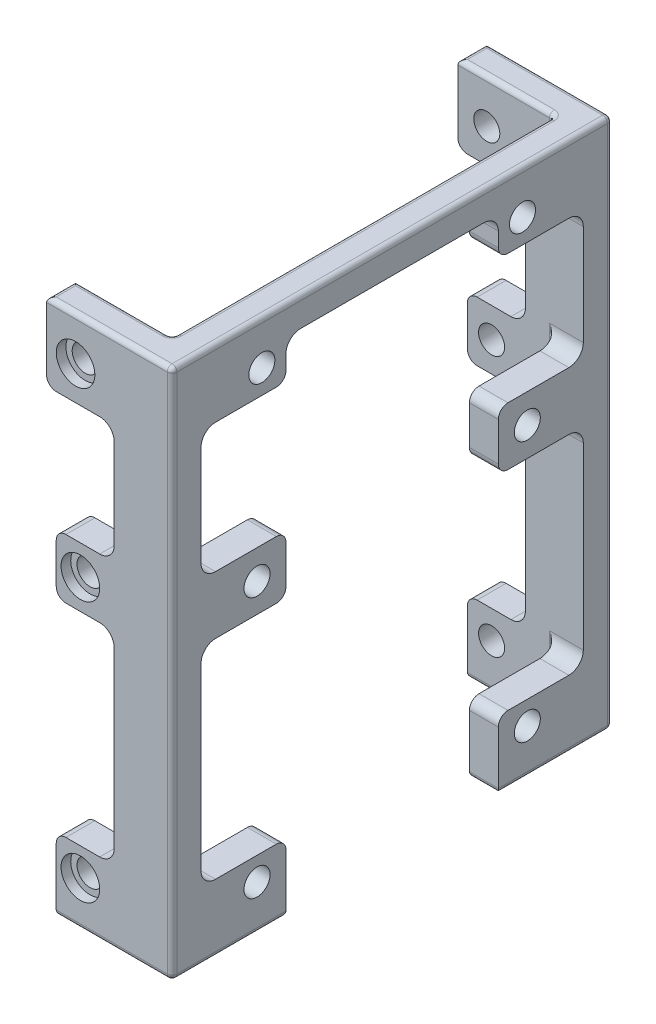
SolidWorks part; units mm, degrees
material "Esun Hard Tough Resin"
ref_plane "Front Plane" through (0, 0, 0) normal (0, 0, 1) x (1, 0, 0)
ref_plane "Top Plane" through (0, 0, 0) normal (0, 1, 0) x (1, 0, 0)
ref_plane "Right Plane" through (0, 0, 0) normal (1, 0, 0) x (0, 0, -1)
sketch "Sketch2" plane through (0, 0, 0) normal (0, 0, 1) x (1, 0, 0)
  line L0 (-6, -15.9661) -> (-6, 28)
  line L1 (6, -28) -> (-6, -28)
  line L2 (6, -28) -> (6, 28)
  line L3 (6, 28) -> (-6, 28)
  line L4 (-6, -28) -> (-6, -15.9661)
  line L5 (6, -28) -> (-6, 28) construction
  line L6 (6, 28) -> (-6, -28) construction
  point P0 (0, 0)
  dimension "D1" = 56
  dimension "D2" = 12
extrude "Boss-Extrude1" add sketch "Sketch2" along normal blind 3
sketch "Sketch3" plane through (0, 0, 0) normal (0, 0, -1) x (-1, 0, 0)
  line L0 (6, -28) -> (-6, -28) construction
  line L1 (-6, 28) -> (-3, 28)
  line L2 (-6, 28) -> (-6, -28)
  line L3 (-6, -28) -> (-3, -28)
  line L4 (-3, 28) -> (-3, -28)
  dimension "D1" = 3
extrude "Boss-Extrude2" add sketch "Sketch3" along normal blind 8.8
sketch "Sketch4" plane through (3, 0, 0) normal (-1, 0, 0) x (0, 0, 1)
  line L0 (-8.8, -28) -> (-8.8, 28) construction
  line L1 (-8.8, 1.6) -> (0, 1.6)
  line L2 (-8.8, 1.6) -> (-8.8, -20)
  line L3 (-8.8, -20) -> (0, -20)
  line L4 (0, 1.6) -> (0, -20)
  line L6 (-8.8, -28) -> (0, -28) construction
  line L7 (0, 28) -> (0, -28) construction
  line L8 (-8.8, 28) -> (0, 28) construction
  line L9 (-8.8, 21) -> (0, 21)
  line L10 (-8.8, 21) -> (-8.8, 7.6)
  line L11 (-8.8, 7.6) -> (0, 7.6)
  line L12 (0, 21) -> (0, 7.6)
  dimension "D1" = 21.6
  dimension "D2" = 8
  dimension "D3" = 13.4
  dimension "D4" = 7
extrude "Cut-Extrude1" cut sketch "Sketch4" against normal through all
sketch "Sketch5" plane through (0, 0, 3) normal (0, 0, 1) x (1, 0, 0)
  line L0 (-6, 28) -> (-6, -28) construction
  line L1 (-6, 1.52) -> (0, 1.52)
  line L2 (-6, 1.52) -> (-6, -19.5)
  line L3 (-6, -19.5) -> (0, -19.5)
  line L4 (0, 1.52) -> (0, -19.5)
  line L5 (6, 28) -> (-6, 28) construction
  line L6 (-6, 20) -> (0, 20)
  line L7 (-6, 20) -> (-6, 7.68)
  line L8 (-6, 7.68) -> (0, 7.68)
  line L9 (0, 20) -> (0, 7.68)
  line L10 (-6, -28) -> (6, -28) construction
  dimension "D1" = 6
  dimension "D2" = 21.02
  dimension "D3" = 12.32
  dimension "D4" = 8
  dimension "D5" = 8.5
extrude "Cut-Extrude2" cut sketch "Sketch5" against normal through all
sketch "Sketch6" plane through (0, 0, 3) normal (0, 0, 1) x (1, 0, 0)
  line L0 (-6, -28) -> (6, -28) construction
  line L1 (0, -19.5) -> (0, 1.52) construction
  line L2 (0, 7.68) -> (0, 20) construction
  circle A0 centre (-4, 23.5) radius 1.35
  circle A1 centre (-3.5, 4.6) radius 1.35
  circle A2 centre (-3.5, -22.4) radius 1.35
  dimension "D1" = 2.7
  dimension "D2" = 18.9
  dimension "D3" = 27
  dimension "D4" = 5.6
  dimension "D5" = 3.5
  dimension "D6" = 3.5
  dimension "D7" = 4
extrude "Cut-Extrude3" cut sketch "Sketch6" against normal through all
sketch "Sketch8" plane through (6, 0, 0) normal (1, 0, 0) x (0, 0, -1)
  line L0 (8.8, 28) -> (8.8, 21) construction
  line L1 (8.8, -20) -> (8.8, -28) construction
  line L2 (-3, -28) -> (8.8, -28) construction
  line L13 (8.8, 7.6) -> (8.8, 1.6) construction
  circle A0 centre (6.3, 23.5) radius 1.35
  circle A1 centre (5.8, 4.6) radius 1.35
  circle A2 centre (5.8, -22.4) radius 1.35
  dimension "D1" = 2.7
  dimension "D2" = 18.9
  dimension "D3" = 27
  dimension "D4" = 2.5
  dimension "D5" = 3
  dimension "D6" = 5.6
  dimension "D9" = 3
extrude "Cut-Extrude5" cut sketch "Sketch8" against normal through all
sketch "Sketch10" plane through (0, 0, -8.8) normal (0, 0, -1) x (-1, 0, 0)
  line L0 (-3, 21) -> (-3, 28) construction
  line L6 (-6, 28) -> (-3, 28)
  line L8 (-6, 28) -> (-6, 25)
  line L9 (-6, 25) -> (-3, 25)
  line L10 (-3, 28) -> (-3, 25)
  dimension "D1" = 3
extrude "Boss-Extrude3" add sketch "Sketch10" along normal blind 11
mirror "Mirror3" about plane through (0, 0, -19.8) normal (0, 0, -1) of bodies 108
sketch "Sketch11" plane through (-6, 0, 0) normal (-1, 0, 0) x (0, 0, 1)
  line L0 (0, 28) -> (0, 20) construction
  line L1 (0, 20) -> (3, 20) construction
  line L2 (3, 20) -> (3, 28) construction
  line L3 (3, 28) -> (0, 28) construction
  line L4 (-39.6, 20) -> (-39.6, 28) construction
  line L5 (-39.6, 28) -> (-42.6, 28) construction
  line L6 (-42.6, 28) -> (-42.6, 20) construction
  line L7 (-42.6, 20) -> (-39.6, 20) construction
  line L8 (0, 28) -> (0, 20)
  line L9 (0, 20) -> (3, 20)
  line L10 (3, 20) -> (3, 28)
  line L11 (3, 28) -> (0, 28)
  line L12 (-39.6, 20) -> (-39.6, 28)
  line L13 (-39.6, 28) -> (-42.6, 28)
  line L14 (-42.6, 28) -> (-42.6, 20)
  line L15 (-42.6, 20) -> (-39.6, 20)
extrude "Boss-Extrude4" add sketch "Sketch11" along normal blind 1
sketch "Sketch12" plane through (0, -28, 0) normal (0, -1, 0) x (1, 0, 0)
  line L1 (6, -42.6) -> (-6, -42.6)
  line L2 (6, -42.6) -> (6, 3)
  line L3 (6, 3) -> (-6, 3)
  line L4 (-6, -42.6) -> (-6, 3)
extrude "Cut-Extrude6" cut sketch "Sketch12" against normal blind 1
fillet "Fillet1" radius 1 16 edges at (-6, 7.68, -41.1) (4.5, 7.6, -30.8) (-6, -19.5, -41.1) (4.5, -20, -30.8) (4.5, 21, -30.8) (4.5, 1.6, -30.8) (-6, 1.52, -41.1) (-7, 20, 1.5) (-7, 20, -41.1) (4.5, -20, -8.8) (4.5, 1.6, -8.8) (4.5, 7.6, -8.8) (4.5, 21, -8.8) (-6, -19.5, 1.5) (-6, 1.52, 1.5) (-6, 7.68, 1.5)
fillet "Fillet2" radius 1.5 18 edges at (0, 1.52, 1.5) (4.5, 1.6, 0) (0, -19.5, 1.5) (4.5, -20, 0) (0, -19.5, -41.1) (4.5, -20, -39.6) (4.5, 7.6, -39.6) (0, 7.68, -41.1) (4.5, 1.6, -39.6) (0, 1.52, -41.1) (0, 20, -41.1) (4.5, 21, -39.6) (4.5, 7.6, 0) (0, 7.68, 1.5) (0, 20, 1.5) (4.5, 21, 0) (4.5, 25, -8.8) (4.5, 25, -30.8)
fillet "Fillet3" radius 0.5 28 edges at (-0.5, 28, -42.6) (3, 4.6, -39.6) (3, 23.75, -39.6) (-2, 28, -39.6) (-2, 28, 0) (3, 28, -19.8) (-7, 28, 1.5) (-7, 28, -41.1) (4.5, -27, -30.8) (3, -22.75, -39.6) (6, 0.5, -42.6) (3, -22.75, 0) (6, 0.5, 3) (-6, -27, 1.5) (6, -27, -2.9) (3, -27, -4.4) (3, -27, -35.2) (-1.5, -27, 0) (4.5, -27, -8.8) (6, -27, -36.7) (0, -27, -42.6) (-6, -27, -41.1) (0, -27, 3) (-1.5, -27, -39.6) (3, 4.6, 0) (3, 23.75, 0) (-0.5, 28, 3) (6, 28, -19.8)
sketch "Sketch13" plane through (3, 0, 0) normal (-1, 0, 0) x (0, 0, 1)
  line L0 (-29.3, 25) -> (-10.3, 25) construction
  line L1 (-29.3, 25) -> (-10.3, 25) construction
  line L2 (-19.8, -993.2431) -> (-19.8, 49006.7569) construction
  circle A0 centre (-33.3, 23.5) radius 2
  circle A1 centre (-33.8, 4.6) radius 2
  circle A2 centre (-33.8, -22.4) radius 2
  circle A3 centre (-5.8, -22.4) radius 2
  circle A4 centre (-5.8, 4.6) radius 2
  circle A5 centre (-6.3, 23.5) radius 2
  point P12 (-19.8, 25)
  dimension "D1" = 4
extrude "Cut-Extrude7" cut sketch "Sketch13" against normal blind 1
sketch "Sketch14" plane through (0, 0, -42.6) normal (0, 0, -1) x (-1, 0, 0)
  circle A0 centre (4, 23.5) radius 2
  circle A1 centre (3.5, 4.6) radius 2
  circle A2 centre (3.5, -22.4) radius 2
  dimension "D1" = 4
extrude "Cut-Extrude8" cut sketch "Sketch14" against normal blind 1
ref_plane "Plane1" through (0, 0, -19.8) normal (0, 0, -1) x (-1, 0, 0)
mirror "Mirror4" about plane through (0, 0, -19.8) normal (0, 0, -1) of "Cut-Extrude8"
